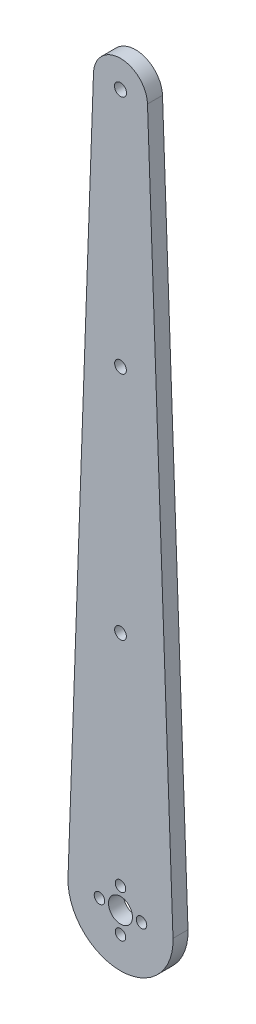
SolidWorks part; units mm, degrees
ref_plane "Front Plane" through (0, 0, 0) normal (0, 0, 1) x (1, 0, 0)
ref_plane "Top Plane" through (0, 0, 0) normal (0, 1, 0) x (1, 0, 0)
ref_plane "Right Plane" through (0, 0, 0) normal (1, 0, 0) x (0, 0, -1)
sketch "Sketch7" plane through (0, 0, 0) normal (0, 0, 1) x (1, 0, 0)
  line L0 (8.9942, 237.1231) -> (17.4887, 0.6282)
  line L1 (-8.9942, 237.1231) -> (-17.4887, 0.6282)
  line L4 (0, 236.8) -> (0, 0) construction
  circle A8 centre (0, 0) radius 4
  arc A11 (-17.4887, 0.6282) -> (17.4887, 0.6282) centre (0, 0) ccw
  circle A12 centre (0, 236.8) radius 2
  arc A13 (8.9942, 237.1231) -> (-8.9942, 237.1231) centre (0, 236.8) ccw
  dimension "D1" = 8
  dimension "D2" = 35
  dimension "D3" = 4
  dimension "D4" = 18
  dimension "D5" = 236.8
extrude "Boss-Extrude1" add sketch "Sketch7" against normal blind 5
sketch "草图2" plane through (0, 0, 0) normal (0, 0, 1) x (1, 0, 0)
  line L0 (0, 236.8) -> (0, 0) construction
  point P4 (0, 80)
  point P5 (0, 156.8)
  dimension "D1" = 80
  dimension "D2" = 80
hole_wizard "M3.5 间隙孔1" positions "3D草图2" profile "草图3" hole size "M3.5" standard "ISO"
sketch3d "3D草图2"
  point P0 (0, 156.8, 0)
  point P3 (0, 80, 0)
sketch "草图3" plane through (0, 156.8, 0) normal (1, 0, 0) x (0, -1, 0)
  line L0 (0, 0) -> (0, 11.1717)
  line L1 (0, 11.1717) -> (1.95, 10)
  line L2 (1.95, 10) -> (1.95, 0)
  line L5 (1.95, 0) -> (0, 0)
  line L10 (0, 11.1717) -> (-1.95, 10) construction
  line L11 (0, -6.35) -> (0, 107.95) construction
  dimension "孔直径" = 3.9
  dimension "孔深度" = 10
  dimension "导头角度" = 118
sketch "草图4" plane through (0, 0, 0) normal (0, 0, 1) x (1, 0, 0)
  line L0 (-7, 0) -> (7, 0) construction
  line L1 (0, -7) -> (0, 7) construction
  circle A0 centre (7, 0) radius 1.75
  circle A1 centre (0, 7) radius 1.75
  circle A2 centre (0, -7) radius 1.75
  circle A3 centre (-7, 0) radius 1.75
  point P8 (0, 0)
  point P9 (0, 0)
  dimension "D1" = 3.5
  dimension "D2" = 3.5
  dimension "D3" = 3.5
  dimension "D4" = 3.5
  dimension "D5" = 14
  dimension "D6" = 14
extrude "切除-拉伸1" cut sketch "草图4" against normal blind 10
